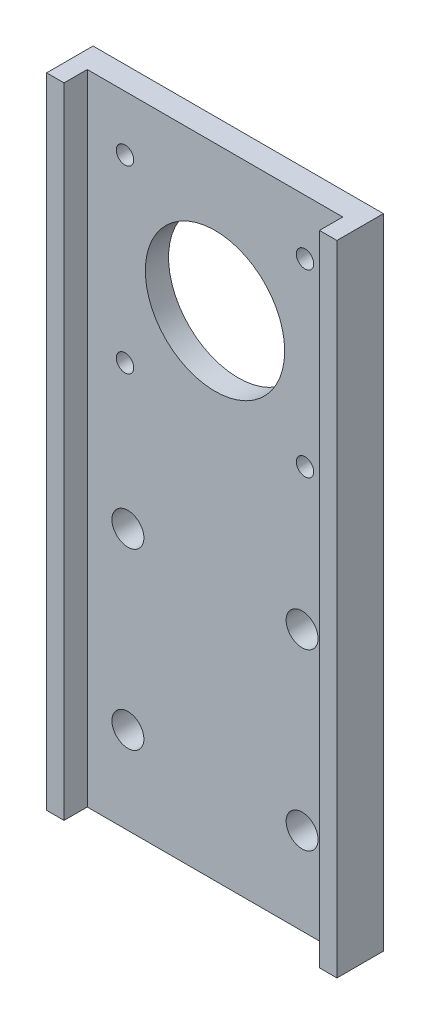
SolidWorks part; units mm, degrees
ref_plane "Front Plane" through (0, 0, 0) normal (0, 0, 1) x (1, 0, 0)
ref_plane "Top Plane" through (0, 0, 0) normal (0, 1, 0) x (1, 0, 0)
ref_plane "Right Plane" through (0, 0, 0) normal (1, 0, 0) x (0, 0, -1)
sketch "Sketch1" plane through (0, 0, 0) normal (0, 0, 1) x (1, 0, 0)
  line L1 (-25, 55) -> (25, 55)
  line L2 (-25, 55) -> (-25, -55)
  line L3 (-25, -55) -> (25, -55)
  line L4 (25, 55) -> (25, -55)
  line L5 (-25, 55) -> (25, -55) construction
  line L6 (-25, -55) -> (25, 55) construction
  point P0 (0, 0)
  dimension "D1" = 50
  dimension "D2" = 110
extrude "Boss-Extrude1" add sketch "Sketch1" along normal blind 4
sketch "Sketch2" plane through (0, 0, 0) normal (0, 0, 1) x (1, 0, 0)
  line L0 (0, -2.2) -> (0, 2.2) construction
  line L1 (25, 55) -> (-25, 55) construction
  line L3 (0, 52.1697) -> (0, 2.1027) construction
  circle A0 centre (-15.5, 45.5) radius 1.5
  circle A1 centre (-15.5, 14.5) radius 1.5
  circle A2 centre (15.5, 14.5) radius 1.5
  circle A3 centre (15.5, 45.5) radius 1.5
  dimension "D1" = 3
  dimension "D2" = 3
  dimension "D3" = 15.5
  dimension "D4" = 15.5
  dimension "D5" = 9.5
  dimension "D6" = 31
extrude "Cut-Extrude1" cut sketch "Sketch2" along normal up to next
sketch "Sketch3" plane through (0, 0, 0) normal (0, 0, 1) x (1, 0, 0)
  line L0 (0, -2.2) -> (0, 2.2) construction
  line L1 (-25, -55) -> (25, -55) construction
  line L2 (0, 13.0646) -> (0, -66.739) construction
  circle A0 centre (-15, -40) radius 2.75
  circle A1 centre (-15, -10) radius 2.75
  circle A2 centre (15, -40) radius 2.75
  circle A3 centre (15, -10) radius 2.75
  dimension "D1" = 5.5
  dimension "D2" = 5.5
  dimension "D3" = 15
  dimension "D4" = 15
  dimension "D5" = 15
  dimension "D6" = 30
extrude "Cut-Extrude2" cut sketch "Sketch3" along normal up to next
sketch "Sketch4" plane through (0, 0, 0) normal (0, 0, 1) x (1, 0, 0)
  line L0 (-25, -55) -> (25, -55) construction
  line L1 (-25, 55) -> (-22, 55)
  line L2 (-25, 55) -> (-25, -55)
  line L3 (-25, -55) -> (-22, -55)
  line L4 (-22, 55) -> (-22, -55)
  line L5 (25, 55) -> (-25, 55) construction
  line L6 (25, -55) -> (22, -55)
  line L7 (25, -55) -> (25, 55)
  line L8 (25, 55) -> (22, 55)
  line L9 (22, -55) -> (22, 55)
  dimension "D1" = 3
  dimension "D2" = 3
extrude "Boss-Extrude2" add sketch "Sketch4" along normal blind 8
sketch "Sketch5" plane through (0, 0, 0) normal (0, 0, 1) x (1, 0, 0)
  line L0 (0, -4.4) -> (0, 4.4) construction
  line L1 (22, 55) -> (-22, 55) construction
  circle A0 centre (0, 30) radius 12
  dimension "D1" = 24
  dimension "D2" = 25
extrude "Cut-Extrude3" cut sketch "Sketch5" along normal up to next
